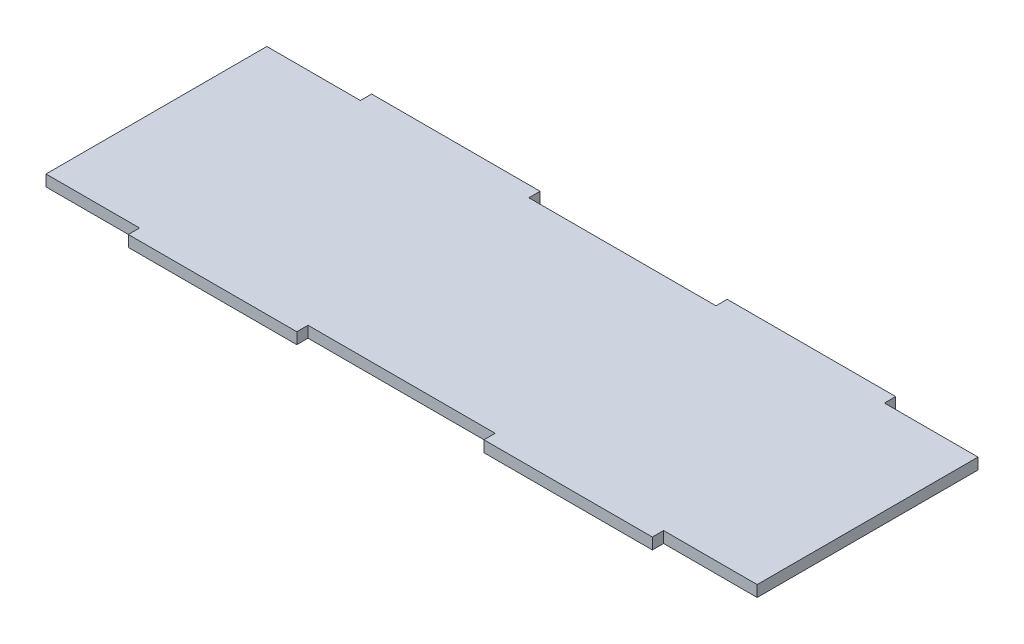
SolidWorks part; units mm, degrees
ref_plane "Front Plane" through (0, 0, 0) normal (0, 0, 1) x (1, 0, 0)
ref_plane "Top Plane" through (0, 0, 0) normal (0, 1, 0) x (1, 0, 0)
ref_plane "Right Plane" through (0, 0, 0) normal (1, 0, 0) x (0, 0, -1)
sketch "Sketch1" plane through (0, 0, 0) normal (0, 1, 0) x (1, 0, 0)
  line L1 (-95, -32.5) -> (95, -32.5)
  line L2 (-95, -32.5) -> (-95, 32.5)
  line L3 (-95, 32.5) -> (95, 32.5)
  line L4 (95, -32.5) -> (95, 32.5)
  line L5 (-95, -32.5) -> (95, 32.5) construction
  line L6 (-95, 32.5) -> (95, -32.5) construction
  point P0 (0, 0)
  dimension "D1" = 65
  dimension "D2" = 190
extrude "Boss-Extrude1" add sketch "Sketch1" along normal blind 3
sketch "Sketch2" plane through (0, 3, 0) normal (0, 1, 0) x (1, 0, 0)
  line L0 (-95, 29.5) -> (-70, 29.5)
  line L1 (-95, 32.5) -> (-95, -32.5) construction
  line L2 (-70, 29.5) -> (-70, 32.5)
  line L3 (95, 32.5) -> (-95, 32.5) construction
  line L4 (-70, 32.5) -> (-25, 32.5)
  line L5 (-25, 32.5) -> (-25, 29.5)
  line L6 (-25, 29.5) -> (25, 29.5)
  line L7 (0, 0) -> (-22.0665, 0) construction
  line L8 (25, 32.5) -> (25, 29.5)
  line L9 (70, 32.5) -> (25, 32.5)
  line L10 (70, 29.5) -> (70, 32.5)
  line L11 (95, 29.5) -> (70, 29.5)
  line L12 (95, -29.5) -> (70, -29.5)
  line L13 (70, -29.5) -> (70, -32.5)
  line L14 (70, -32.5) -> (25, -32.5)
  line L15 (25, -32.5) -> (25, -29.5)
  line L16 (-25, -29.5) -> (25, -29.5)
  line L17 (-25, -32.5) -> (-25, -29.5)
  line L18 (-70, -32.5) -> (-25, -32.5)
  line L19 (-70, -29.5) -> (-70, -32.5)
  line L20 (-95, -29.5) -> (-70, -29.5)
  line L21 (-95, 29.5) -> (-95, -29.5)
  line L22 (95, 29.5) -> (95, -29.5)
  point P14 (0, 29.5)
  point P28 (0, -29.5)
  dimension "D1" = 25
  dimension "D2" = 25
  dimension "D3" = 3
  dimension "D4" = 3
  dimension "D5" = 3
  dimension "D6" = 3
extrude "Cut-Extrude1" cut sketch "Sketch2" against normal blind 3 and the other way through all flip side to cut
